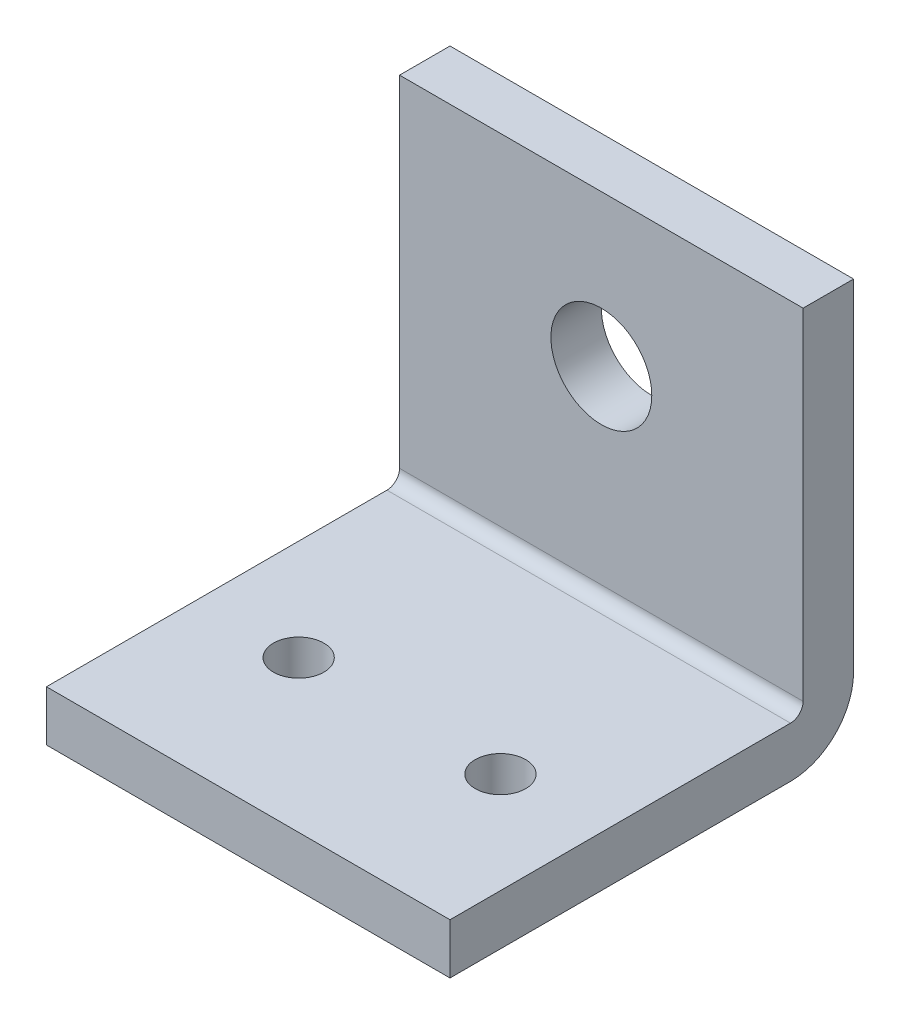
SolidWorks part; units mm, degrees
ref_plane "Front Plane" through (0, 0, 0) normal (0, 0, 1) x (1, 0, 0)
ref_plane "Top Plane" through (0, 0, 0) normal (0, 1, 0) x (1, 0, 0)
ref_plane "Right Plane" through (0, 0, 0) normal (1, 0, 0) x (0, 0, -1)
sketch "Sketch1" plane through (0, 0, 0) normal (0, 1, 0) x (1, 0, 0)
  line L0 (0, 0) -> (40, 0)
  line L1 (40, 0) -> (40, 40)
  line L2 (40, 40) -> (0, 40)
  line L3 (0, 40) -> (0, 0)
  circle A0 centre (10, 15) radius 2.5
  circle A1 centre (30, 15) radius 2.5
  dimension "D3" = 5
  dimension "D1" = 40
  dimension "D2" = 40
  dimension "D4" = 10
  dimension "D5" = 10
  dimension "D6" = 15
  dimension "D7" = 15
extrude "Boss-Extrude1" add sketch "Sketch1" along normal blind 5
sketch "Sketch2" plane through (0, 5, 0) normal (0, 1, 0) x (1, 0, 0)
  line L0 (0, 40) -> (40, 40)
  line L1 (40, 40) -> (40, 35)
  line L2 (40, 0) -> (40, 40) construction
  line L3 (40, 35) -> (0, 35)
  line L4 (0, 40) -> (0, 0) construction
  line L5 (0, 35) -> (0, 40)
  dimension "D1" = 5
extrude "Boss-Extrude2" add sketch "Sketch2" along normal blind 35
sketch "Sketch3" plane through (0, 0, -35) normal (0, 0, 1) x (1, 0, 0)
  line L0 (0, 40) -> (40, 40) construction
  line L1 (40, 40) -> (40, 5) construction
  circle A0 centre (20, 25) radius 5
  dimension "D1" = 10
  dimension "D2" = 15
  dimension "D3" = 20
extrude "Cut-Extrude1" cut sketch "Sketch3" against normal blind 35
fillet "Fillet1" radius 6.25 1 edges at (20, 0, -40)
fillet "Fillet2" radius 1.25 1 edges at (20, 5, -35)
